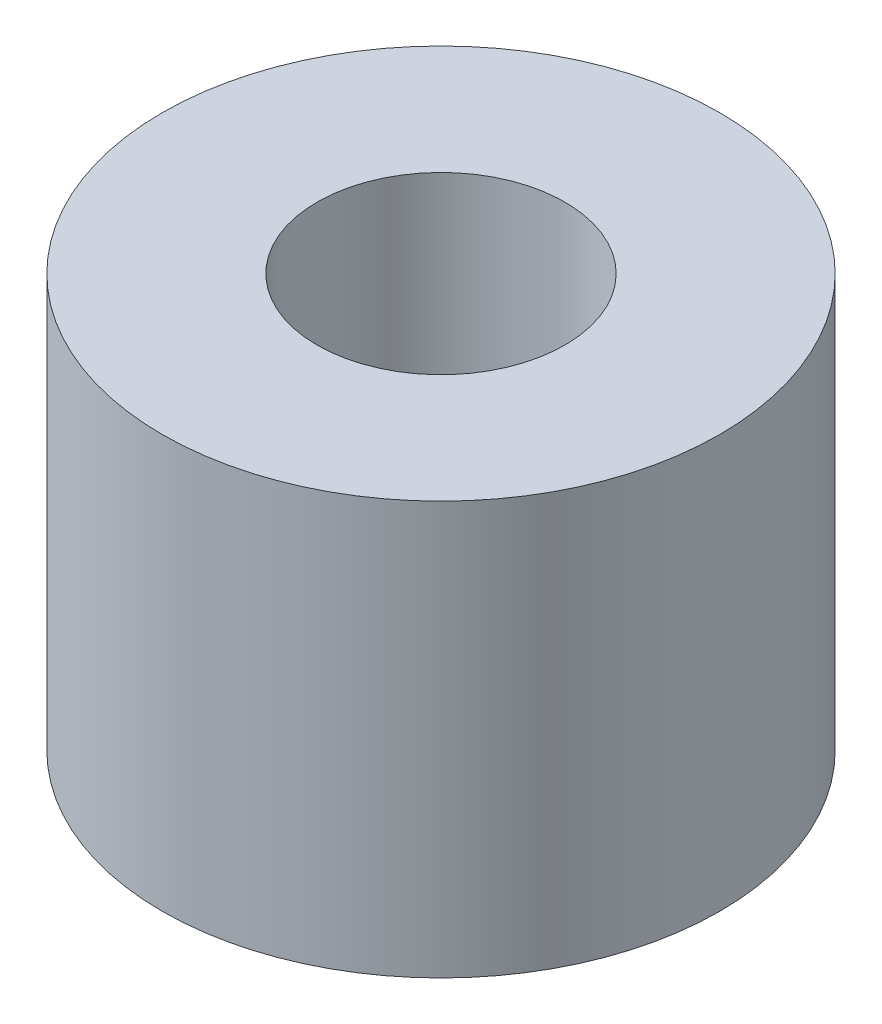
SolidWorks part; units mm, degrees
material "6061-T6 (SS)"
ref_plane "Front Plane" through (0, 0, 0) normal (0, 0, 1) x (1, 0, 0)
ref_plane "Top Plane" through (0, 0, 0) normal (0, 1, 0) x (1, 0, 0)
ref_plane "Right Plane" through (0, 0, 0) normal (1, 0, 0) x (0, 0, -1)
sketch "Sketch1" plane through (0, 0, 0) normal (1, 0, 0) x (0, 0, -1)
  line L0 (0, 10.0184) -> (0, -7.2934) construction
  line L2 (2.3812, -3.9688) -> (5.3578, -3.9688)
  line L3 (2.3812, -3.9688) -> (2.3812, 3.9687)
  line L4 (2.3812, 3.9687) -> (5.3578, 3.9688)
  line L5 (5.3578, -3.9688) -> (5.3578, 3.9688)
  line L6 (2.3812, -3.9688) -> (5.3578, 3.9688) construction
  line L7 (2.3812, 3.9687) -> (5.3578, -3.9688) construction
  point P7 (3.8695, 0)
  dimension "D1" = 4.7625
  dimension "D2" = 10.7156
  dimension "D3" = 7.9375
revolve "Revolve1" add sketch "Sketch1" angle 360 about L0
